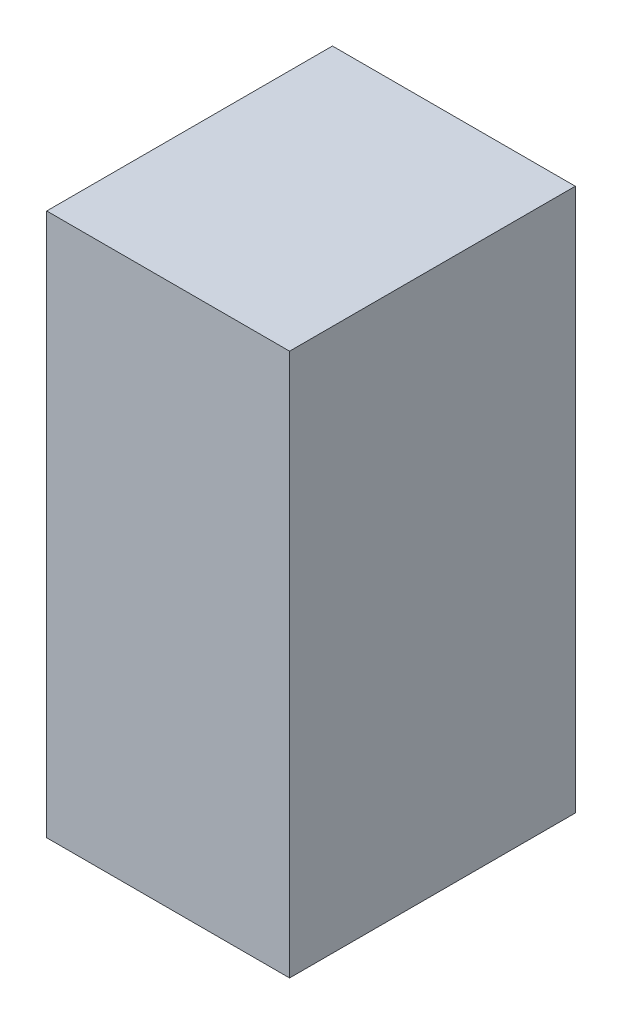
SolidWorks part; units mm, degrees
material "普通碳钢"
ref_plane "前视基准面" through (0, 0, 0) normal (0, 0, 1) x (1, 0, 0)
ref_plane "上视基准面" through (0, 0, 0) normal (0, 1, 0) x (1, 0, 0)
ref_plane "右视基准面" through (0, 0, 0) normal (1, 0, 0) x (0, 0, -1)
sketch "草图2" plane through (0, 0, 0) normal (0, 0, 1) x (1, 0, 0)
  line L1 (-0.0425, 0.095) -> (0.0425, 0.095)
  line L2 (-0.0425, 0.095) -> (-0.0425, -0.095)
  line L3 (-0.0425, -0.095) -> (0.0425, -0.095)
  line L4 (0.0425, 0.095) -> (0.0425, -0.095)
  line L5 (-0.0425, 0.095) -> (0.0425, -0.095) construction
  line L6 (-0.0425, -0.095) -> (0.0425, 0.095) construction
  point P0 (0, 0)
extrude "凸台-拉伸1" add sketch "草图2" along normal blind 0.1
